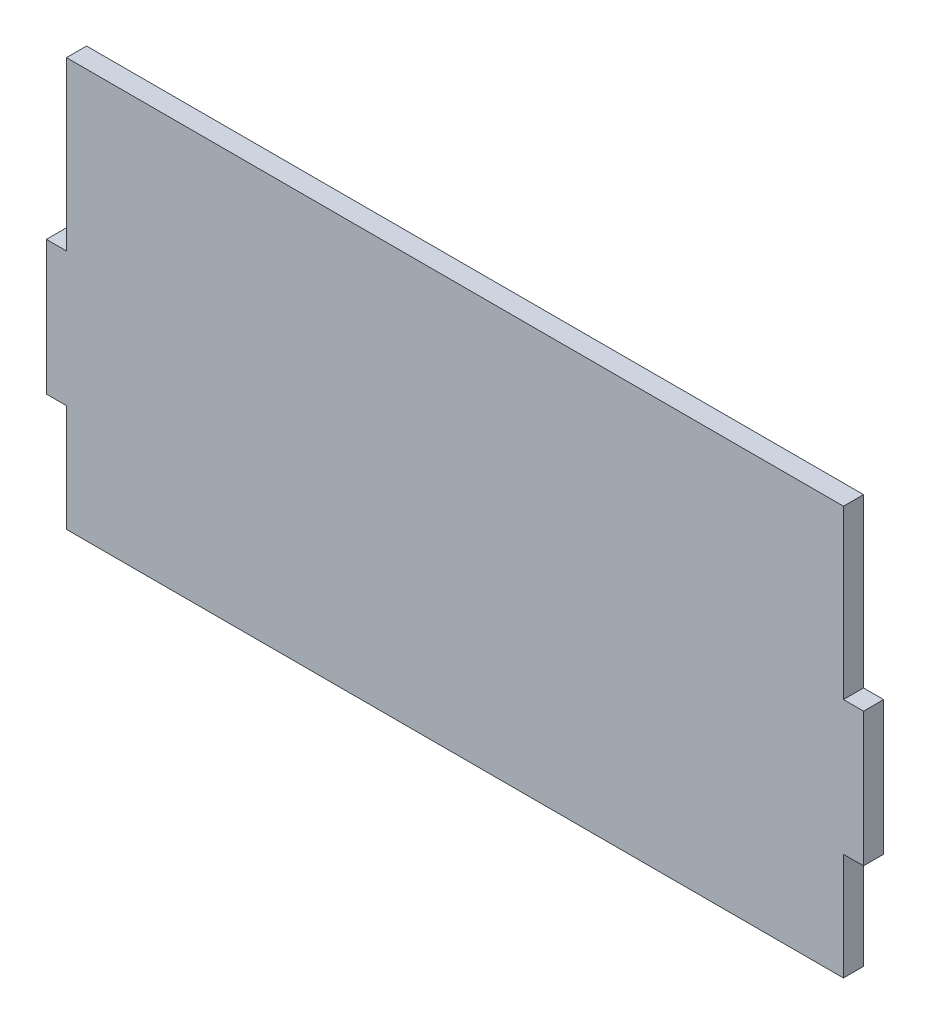
SolidWorks part; units mm, degrees
material "A-Glass Fiber"
ref_plane "Front Plane" through (0, 0, 0) normal (0, 0, 1) x (1, 0, 0)
ref_plane "Top Plane" through (0, 0, 0) normal (0, 1, 0) x (1, 0, 0)
ref_plane "Right Plane" through (0, 0, 0) normal (1, 0, 0) x (0, 0, -1)
sketch "Sketch1" plane through (0, 0, 0) normal (0, 0, 1) x (1, 0, 0)
  line L0 (-58, 35) -> (58, 35)
  line L1 (58, 35) -> (58, 10)
  line L2 (58, 10) -> (61, 10)
  line L3 (61, 10) -> (61, -10)
  line L4 (61, -10) -> (58, -10)
  line L5 (58, -10) -> (58, -26)
  line L6 (58, -26) -> (-58, -26)
  line L7 (-58, -26) -> (-58, -10)
  line L8 (-58, -10) -> (-61, -10)
  line L9 (-61, -10) -> (-61, 10)
  line L10 (-61, 10) -> (-58, 10)
  line L11 (-58, 10) -> (-58, 35)
  line L12 (-61, 0) -> (61, 0) construction
  point P14 (0, 0)
  dimension "D1" = 3
  dimension "D2" = 20
  dimension "D3" = 116
  dimension "D4" = 25
  dimension "D5" = 16
extrude "Boss-Extrude1" add sketch "Sketch1" along normal blind 3
